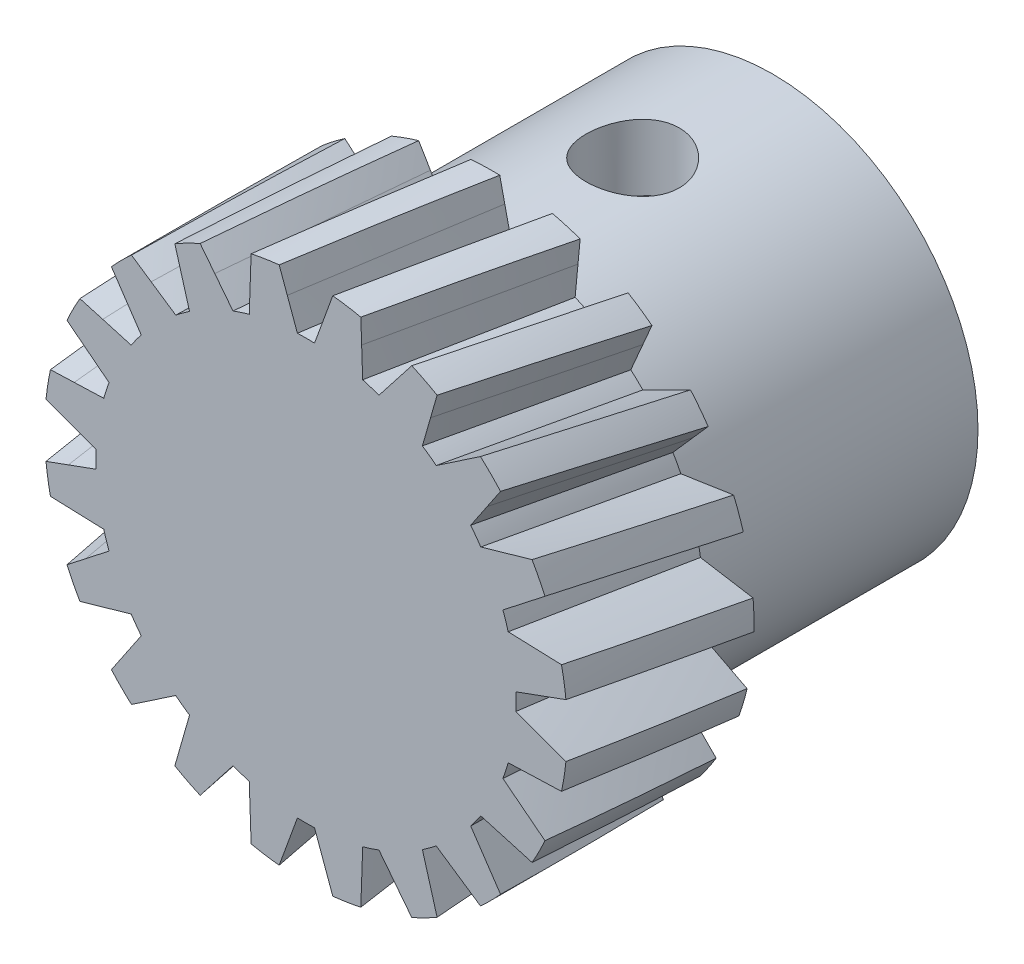
SolidWorks part; units mm, degrees
ref_plane "Front Plane" through (0, 0, 0) normal (0, 0, 1) x (1, 0, 0)
ref_plane "Top Plane" through (0, 0, 0) normal (0, 1, 0) x (1, 0, 0)
ref_plane "Right Plane" through (0, 0, 0) normal (1, 0, 0) x (0, 0, -1)
sketch "Sketch1" plane through (0, 0, 0) normal (0, 0, 1) x (1, 0, 0)
  circle A0 centre (0, 0) radius 14
  dimension "D1" = 28
extrude "Boss-Extrude1" add sketch "Sketch1" along normal blind 10
sketch "Sketch2" plane through (0, 0, 10) normal (0, 0, 1) x (1, 0, 0)
  line L0 (0, 0) -> (0, 14.1924) construction
  line L3 (1, 12.73) -> (1.5032, 14.1126)
  line L4 (-1, 12.73) -> (-0.4579, 11.2407)
  line L5 (1, 12.73) -> (0.4579, 11.2407)
  line L10 (-1, 12.73) -> (-1.5032, 14.1126)
  arc A0 (1.5032, 14.1126) -> (-1.5032, 14.1126) centre (0, 0) ccw
  arc A2 (0.4579, 11.2407) -> (-0.4579, 11.2407) centre (0, 0) ccw
  dimension "D2" = 22.5
  dimension "D3" = 20
sketch "Sketch4" plane through (0, 0, 0) normal (0, 0, -1) x (-1, 0, 0)
  line L0 (0, 0) -> (0, 23.1416) construction
  line L1 (0, 0) -> (-3.3616, 25.9181) construction
  line L4 (-2.6341, 12.5345) -> (-3.288, 13.7965)
  line L5 (-0.6507, 12.7918) -> (-0.3404, 14.1788)
  line L6 (-2.6341, 12.5345) -> (-1.8861, 11.0908)
  line L7 (-0.6507, 12.7918) -> (-1.0057, 11.205)
  line L8 (0, 7.4507) -> (0.4912, 6.5026)
  arc A0 (-0.3404, 14.1788) -> (-3.288, 13.7965) centre (0, 0) ccw
  arc A2 (-1.0057, 11.205) -> (-1.8861, 11.0908) centre (0, 0) ccw
  dimension "D1" = 7.39
sketch "Sketch6" plane through (0, 0, 0) normal (0, 0, -1) x (-1, 0, 0)
  circle A0 centre (0, 0) radius 11
  circle A1 centre (0, 0) radius 7.5
extrude "Boss-Extrude2" add sketch "Sketch6" along normal blind 15
ref_plane "Plane2" through (3.1865, 0, 0.5687) normal (0.9844, 0, 0.1757) x (0.1757, 0, -0.9844)
sketch "Sketch8" plane through (3.1865, 0, 0.5687) normal (0.9844, 0, 0.1757) x (0.1757, 0, -0.9844)
  line L0 (0.5777, 13.7965) -> (-9.5803, 14.1126)
loft "Cut-Loft3" cut profiles "Sketch2" section "Sketch2" section "Sketch4"
pattern_circular "CirPattern3" count 20 over 360 of "Cut-Loft3"
sketch "Sketch9" plane through (0, 0, 10) normal (0, 0, 1) x (1, 0, 0)
  circle A0 centre (0, 0) radius 12.73
  dimension "D1" = 25.46
sketch "Sketch10" plane through (0, 0, 0) normal (0, 1, 0) x (1, 0, 0)
  line L0 (0, 15) -> (0, 7.5) construction
  line L1 (11, 15) -> (-11, 15) construction
  circle A0 centre (0, 7.5) radius 2.5
extrude "Cut-Extrude5" cut sketch "Sketch10" along normal blind 25 and the other way blind 29
